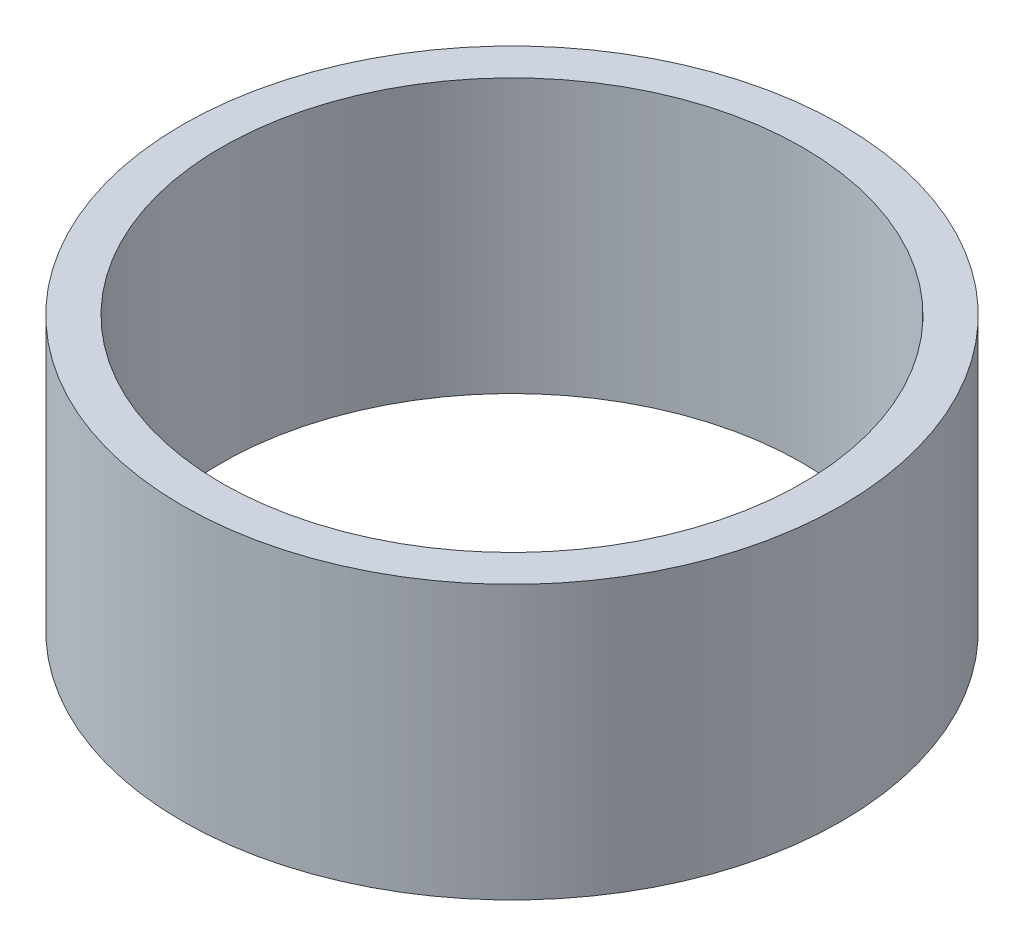
SolidWorks part; units mm, degrees
ref_plane "Front Plane" through (0, 0, 0) normal (0, 0, 1) x (1, 0, 0)
ref_plane "Top Plane" through (0, 0, 0) normal (0, 1, 0) x (1, 0, 0)
ref_plane "Right Plane" through (0, 0, 0) normal (1, 0, 0) x (0, 0, -1)
sketch "Sketch1" plane through (0, 0, 0) normal (0, 1, 0) x (1, 0, 0)
  circle A0 centre (0, 0) radius 42.2137
  circle A1 centre (0, 0) radius 37.2137
  dimension "D1" = 5
extrude "Boss-Extrude1" add sketch "Sketch1" along normal blind 35 contours A0 | A1
sketch "Sketch2" plane through (0, 35, 0) normal (0, 1, 0) x (1, 0, 0)
  line L0 (-35.5737, -10.9256) -> (-25.904, -33.3313)
  line L1 (-25.904, -33.3313) -> (0.4492, -37.2109)
  line L2 (-21.3837, 30.4564) -> (-39.7047, 14.3362)
  line L3 (-39.7047, 14.3362) -> (-35.2509, -11.926)
  line L4 (22.3579, 29.7487) -> (1.3651, 42.1916)
  line L5 (1.3651, 42.1916) -> (-22.2354, 29.8403)
  line L6 (35.2016, -12.0707) -> (40.5484, 11.7396)
  line L7 (40.5484, 11.7396) -> (21.5087, 30.3683)
  line L8 (-0.6021, -37.2088) -> (23.6952, -34.9361)
  line L9 (23.6952, -34.9361) -> (35.5285, -11.0716)
  circle A0 centre (0, 0) radius 37.2137 construction
  circle A1 centre (0, 0) radius 42.2137 construction
  point P7 (0, 0)
  point P8 (-35.9343, -11.0208)
  point P21 (0, 0)
  point P22 (-21.3115, 30.507)
  point P23 (-35.2016, -12.0707)
  dimension "D4" = 5
